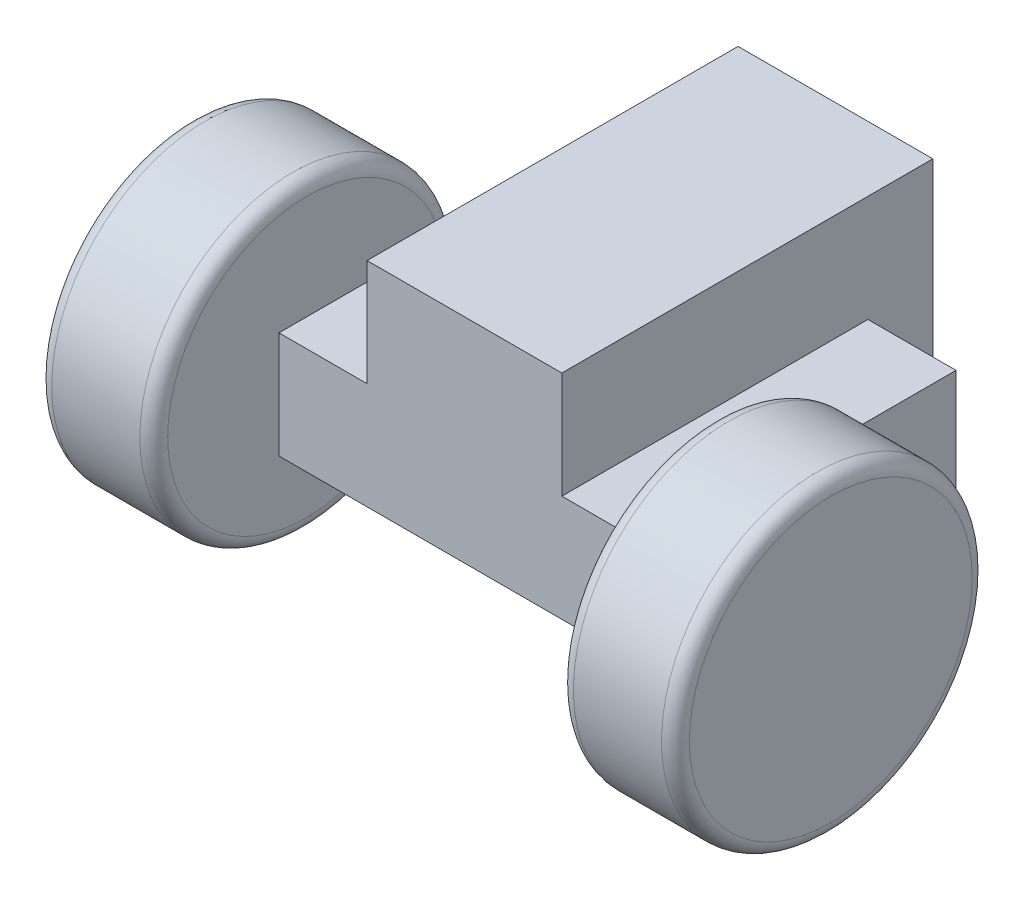
SolidWorks part; units mm, degrees
ref_plane "Front Plane" through (0, 0, 0) normal (0, 0, 1) x (1, 0, 0)
ref_plane "Top Plane" through (0, 0, 0) normal (0, 1, 0) x (1, 0, 0)
ref_plane "Right Plane" through (0, 0, 0) normal (1, 0, 0) x (0, 0, -1)
sketch "Sketch2" plane through (0, 0, 0) normal (0, 1, 0) x (1, 0, 0)
  line L1 (34.9697, 40.1515) -> (76.9697, 40.1515)
  line L2 (34.9697, 40.1515) -> (34.9697, -39.8485)
  line L3 (34.9697, -39.8485) -> (76.9697, -39.8485)
  line L4 (76.9697, 40.1515) -> (76.9697, -39.8485)
  dimension "D1" = 80
  dimension "D2" = 42
extrude "Boss-Extrude1" add sketch "Sketch2" along normal blind 46 contours L1 L4 L3 L2
sketch "Sketch3" plane through (76.9697, 0, 0) normal (1, 0, 0) x (0, 0, -1)
  line L1 (-39.8485, 0) -> (26.1515, 0)
  line L2 (-39.8485, 0) -> (-39.8485, 23)
  line L3 (-39.8485, 23) -> (26.1515, 23)
  line L4 (26.1515, 0) -> (26.1515, 23)
  dimension "D1" = 23
  dimension "D2" = 66
extrude "Boss-Extrude2" add sketch "Sketch3" along normal blind 19
sketch "Sketch4" plane through (95.9697, 0, 0) normal (1, 0, 0) x (0, 0, -1)
  line L0 (-39.8485, 23) -> (-39.8485, 0) construction
  line L3 (26.1515, 23) -> (-39.8485, 23) construction
  circle A0 centre (-29.8485, 11.5) radius 5
  dimension "D1" = 10
  dimension "D2" = 11.5
  dimension "D3" = 10
extrude "Boss-Extrude3" add sketch "Sketch4" along normal blind 4
sketch "Sketch5" plane through (99.9697, 0, 0) normal (1, 0, 0) x (0, 0, -1)
  circle A0 centre (-29.8485, 11.5) radius 33.5
  dimension "D1" = 67
extrude "Boss-Extrude4" add sketch "Sketch5" along normal blind 25
sketch "Sketch6" plane through (34.9697, 0, 0) normal (-1, 0, 0) x (0, 0, 1)
  line L1 (39.8485, 0) -> (-26.1515, 0)
  line L2 (39.8485, 0) -> (39.8485, 23)
  line L3 (39.8485, 23) -> (-26.1515, 23)
  line L4 (-26.1515, 0) -> (-26.1515, 23)
  dimension "D1" = 23
  dimension "D2" = 66
extrude "Boss-Extrude5" add sketch "Sketch6" along normal blind 19
sketch "Sketch8" plane through (15.9697, 0, 0) normal (-1, 0, 0) x (0, 0, 1)
  line L0 (39.8485, 23) -> (-26.1515, 23) construction
  line L1 (39.8485, 0) -> (39.8485, 23) construction
  circle A0 centre (29.8485, 11.5) radius 5
  dimension "D1" = 10
  dimension "D2" = 11.5
  dimension "D3" = 10
extrude "Boss-Extrude6" add sketch "Sketch8" along normal blind 4
sketch "Sketch10" plane through (11.9697, 0, 0) normal (-1, 0, 0) x (0, 0, 1)
  circle A0 centre (29.8485, 11.5) radius 33
  dimension "D1" = 66
extrude "Boss-Extrude7" add sketch "Sketch10" along normal blind 25
fillet "Fillet2" radius 3 4 edges at (124.9697, 11.5, -3.6515) (99.9697, 11.5, -3.6515) (11.9697, 11.5, 62.8485) (-13.0303, 11.5, 62.8485)
